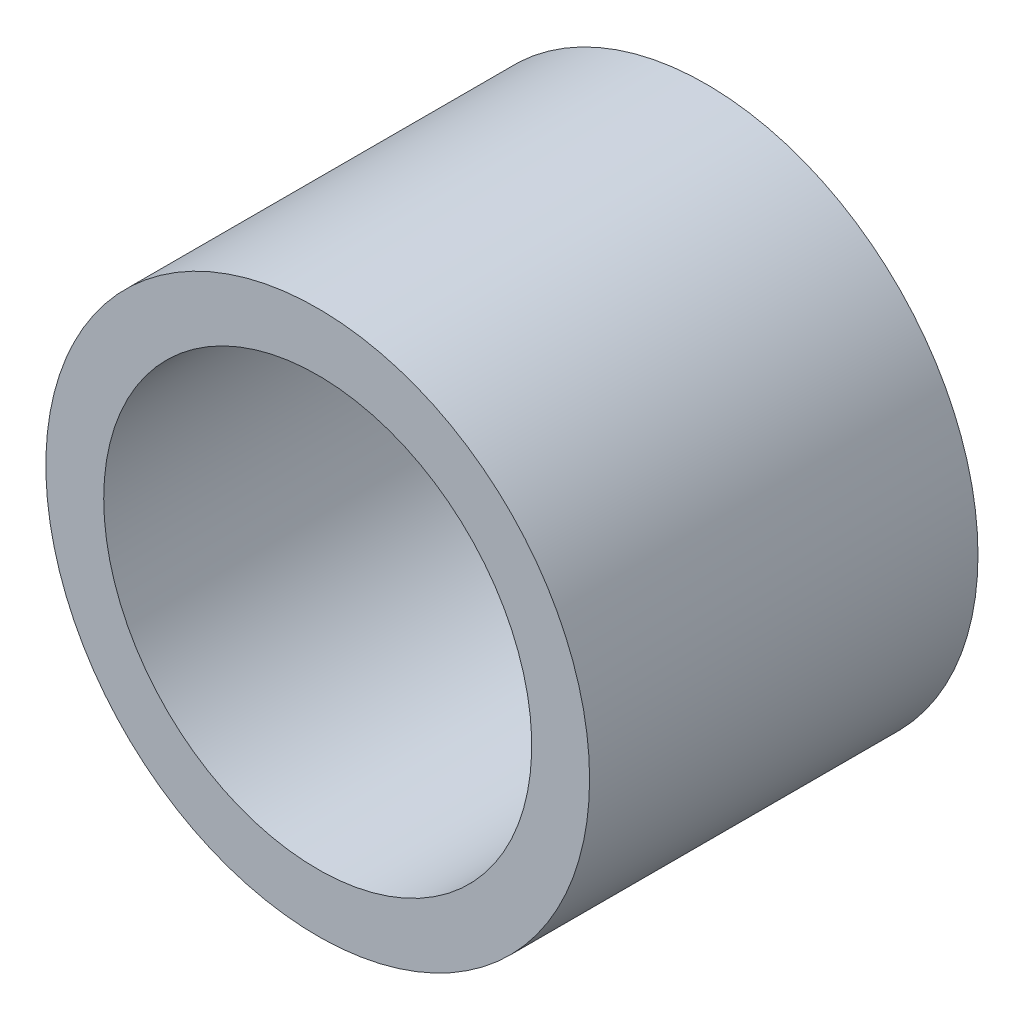
SolidWorks part; units mm, degrees
ref_plane "前视基准面" through (0, 0, 0) normal (0, 0, 1) x (1, 0, 0)
ref_plane "上视基准面" through (0, 0, 0) normal (0, 1, 0) x (1, 0, 0)
ref_plane "右视基准面" through (0, 0, 0) normal (1, 0, 0) x (0, 0, -1)
other "Configuration Table"
sketch "草图1" plane through (0, 0, 0) normal (0, 0, 1) x (1, 0, 0)
  circle A1 centre (0, 0) radius 14
extrude "凸台-拉伸2" add sketch "草图1" along normal blind 20
sketch "草图4" plane through (0, 0, 0) normal (0, 0, -1) x (-1, 0, 0)
  circle A1 centre (0, 0) radius 11.02
extrude "切除-拉伸2" cut sketch "草图4" against normal through all
